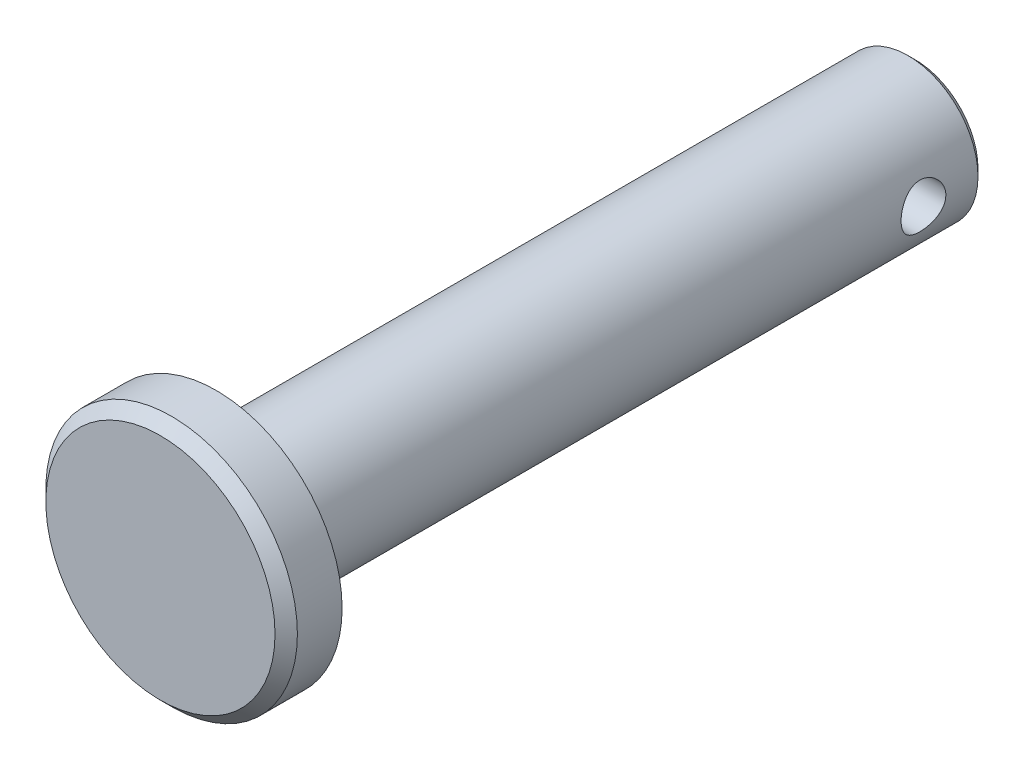
SolidWorks part; units mm, degrees
ref_plane "Front" through (0, 0, 0) normal (0, 0, 1) x (1, 0, 0)
ref_plane "Top" through (0, 0, 0) normal (0, 1, 0) x (1, 0, 0)
ref_plane "Right" through (0, 0, 0) normal (1, 0, 0) x (0, 0, -1)
sketch "Sketch1" plane through (0, 0, 0) normal (0, 0, 1) x (1, 0, 0)
  circle A0 centre (0, 0) radius 5
  point P3 (0, 5)
  point P4 (0, -5)
  dimension "dia" = 10
extrude "Extrude1" add sketch "Sketch1" along normal mid plane 50
sketch "Sketch2" plane through (0, 0, 25) normal (0, 0, 1) x (1, 0, 0)
  circle A0 centre (0, 0) radius 9
  dimension "head dia" = 18
extrude "Extrude2" add sketch "Sketch2" along normal blind 4
chamfer "Chamfer1" distance 0.8 angle 45 1 edges at (9, 0, 29)
sketch "Sketch3" plane through (0, 0, 0) normal (1, 0, 0) x (0, 0, -1)
  line L0 (-25, -5) -> (-25, 5) construction
  circle A0 centre (20.6, 0) radius 1.6
  point P2 (19, 0)
  dimension "hole dia" = 3.2
  dimension "useable Lg" = 44
extrude "Extrude3" cut sketch "Sketch3" against normal through all and the other way through all
chamfer "Chamfer2" distance 0.5 angle 45 1 edges at (5, 0, -25)
ref_plane "Plane1" through (0, 0, -20.6) normal (0, 0, 1) x (1, 0, 0)
sketch "Sketch8" plane through (0, 0, 0) normal (1, 0, 0) x (0, 0, -1)
  line L0 (-29, 8.2) -> (-29, -8.2) construction
  line L1 (-28.2, -9) -> (-25, -9) construction
  line L2 (25, -4.5) -> (25, 4.5) construction
  point P0 (-29, 9)
  point P1 (-25, 9)
  point P5 (25, 5)
  point P8 (-29, -9)
  point P9 (25, -5)
equation "\"D1@Chamfer1\" = \"head ht@Extrude2\" * .2"
equation "\"D1@Chamfer2\" = \"dia@Sketch1\" * .05"
